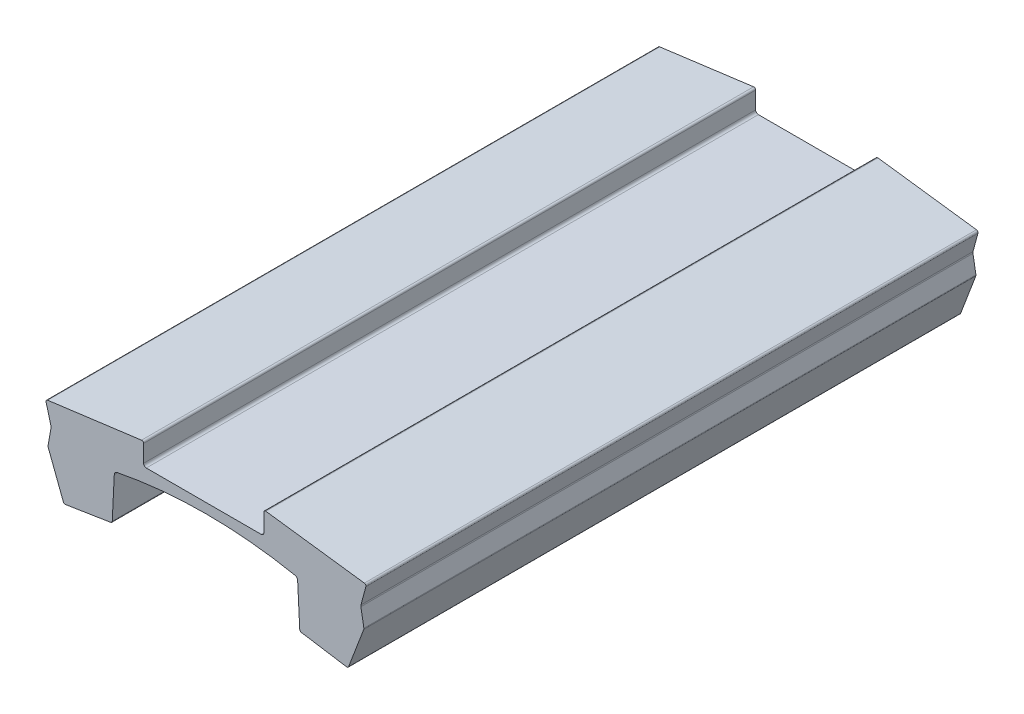
SolidWorks part; units mm, degrees
ref_plane "Ön Düzlem" through (0, 0, 0) normal (0, 0, 1) x (1, 0, 0)
ref_plane "Üst Düzlem" through (0, 0, 0) normal (0, 1, 0) x (1, 0, 0)
ref_plane "Sağ Düzlem" through (0, 0, 0) normal (1, 0, 0) x (0, 0, -1)
sketch "Sketch1" plane through (0, 0, 0) normal (0, 0, 1) x (1, 0, 0)
  line L209 (-17.6248, 90.5561) -> (-17.082, 88.5301)
  line L220 (-17.4061, 86.4651) -> (-17.0743, 88.3575)
  line L221 (-17.396, 86.3593) -> (-15.7146, 81.9531)
  line L222 (-15.4964, 81.8269) -> (-10.4958, 82.6189)
  line L223 (-10.3274, 82.8065) -> (-10.1019, 87.3646)
  line L224 (10.3511, 82.8056) -> (10.1212, 87.365)
  line L225 (15.5201, 81.8261) -> (10.5196, 82.6181)
  line L226 (17.4151, 86.3593) -> (15.7384, 81.9525)
  line L227 (17.0934, 88.3575) -> (17.4252, 86.4649)
  line L228 (17.6439, 90.5561) -> (17.101, 88.5301)
  line L229 (6.6156, 92.2361) -> (17.4768, 90.8062)
  line L231 (6.3895, 92.0378) -> (6.3895, 90.0739)
  line L232 (-6.5705, 89.7739) -> (6.0895, 89.7739)
  line L233 (-6.8705, 91.9719) -> (-6.8705, 90.0739)
  line L234 (-17.4578, 90.8062) -> (-7.0966, 92.1702)
  arc A73 (6.3895, 92.0378) -> (6.6156, 92.2361) centre (6.5895, 92.0378) cw
  arc A74 (-17.082, 88.5301) -> (-17.0743, 88.3575) centre (-17.4683, 88.4265) cw
  arc A75 (-17.396, 86.3593) -> (-17.4061, 86.4651) centre (-17.2091, 86.4306) cw
  arc A76 (-6.8705, 91.9719) -> (-7.0966, 92.1702) centre (-7.0705, 91.9719) ccw
  arc A93 (-15.7146, 81.9531) -> (-15.4964, 81.8269) centre (-15.5277, 82.0244) ccw
  arc A94 (-10.4958, 82.6189) -> (-10.3274, 82.8065) centre (-10.5271, 82.8164) ccw
  arc A95 (-9.7798, 87.7373) -> (-10.1019, 87.3646) centre (-9.7024, 87.3449) ccw
  arc A96 (-9.7798, 87.7373) -> (9.7991, 87.7373) centre (0.0095, 38.0933) cw
  arc A97 (10.1212, 87.365) -> (9.7991, 87.7373) centre (9.7217, 87.3448) ccw
  arc A98 (10.3511, 82.8056) -> (10.5196, 82.6181) centre (10.5509, 82.8157) ccw
  arc A99 (15.5201, 81.8261) -> (15.7384, 81.9525) centre (15.5514, 82.0237) ccw
  arc A100 (17.4151, 86.3593) -> (17.4252, 86.4649) centre (17.2282, 86.4304) ccw
  arc A101 (17.101, 88.5301) -> (17.0934, 88.3575) centre (17.4874, 88.4265) ccw
  arc A102 (17.4768, 90.8062) -> (17.6439, 90.5561) centre (17.4507, 90.6079) cw
  arc A107 (-17.4578, 90.8062) -> (-17.6248, 90.5561) centre (-17.4317, 90.6079) ccw
  arc A108 (6.3895, 90.0739) -> (6.0895, 89.7739) centre (6.0895, 90.0739) cw
  arc A109 (-6.5705, 89.7739) -> (-6.8705, 90.0739) centre (-6.5705, 90.0739) cw
  dimension "D1" = 0.2
  dimension "D2" = 0.3
extrude "Boss-Extrude2" add sketch "Sketch1" along normal blind 67.5
